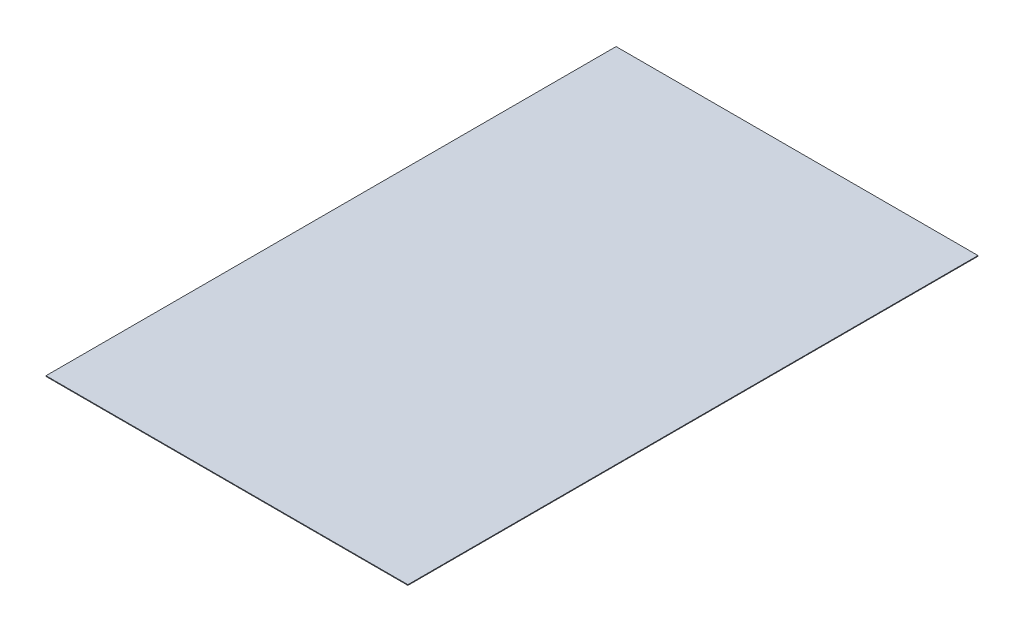
SolidWorks part; units mm, degrees
ref_plane "Front Plane" through (0, 0, 0) normal (0, 0, 1) x (1, 0, 0)
ref_plane "Top Plane" through (0, 0, 0) normal (0, 1, 0) x (1, 0, 0)
ref_plane "Right Plane" through (0, 0, 0) normal (1, 0, 0) x (0, 0, -1)
sketch "Sketch1" plane through (0, 0, 0) normal (0, 1, 0) x (1, 0, 0)
  line L1 (0, 0) -> (5320, 0)
  line L2 (0, 0) -> (0, -8380)
  line L3 (0, -8380) -> (5320, -8380)
  line L4 (5320, 0) -> (5320, -8380)
  dimension "D1" = 5320
  dimension "D2" = 8380
extrude "Boss-Extrude1" add sketch "Sketch1" along normal blind 10
